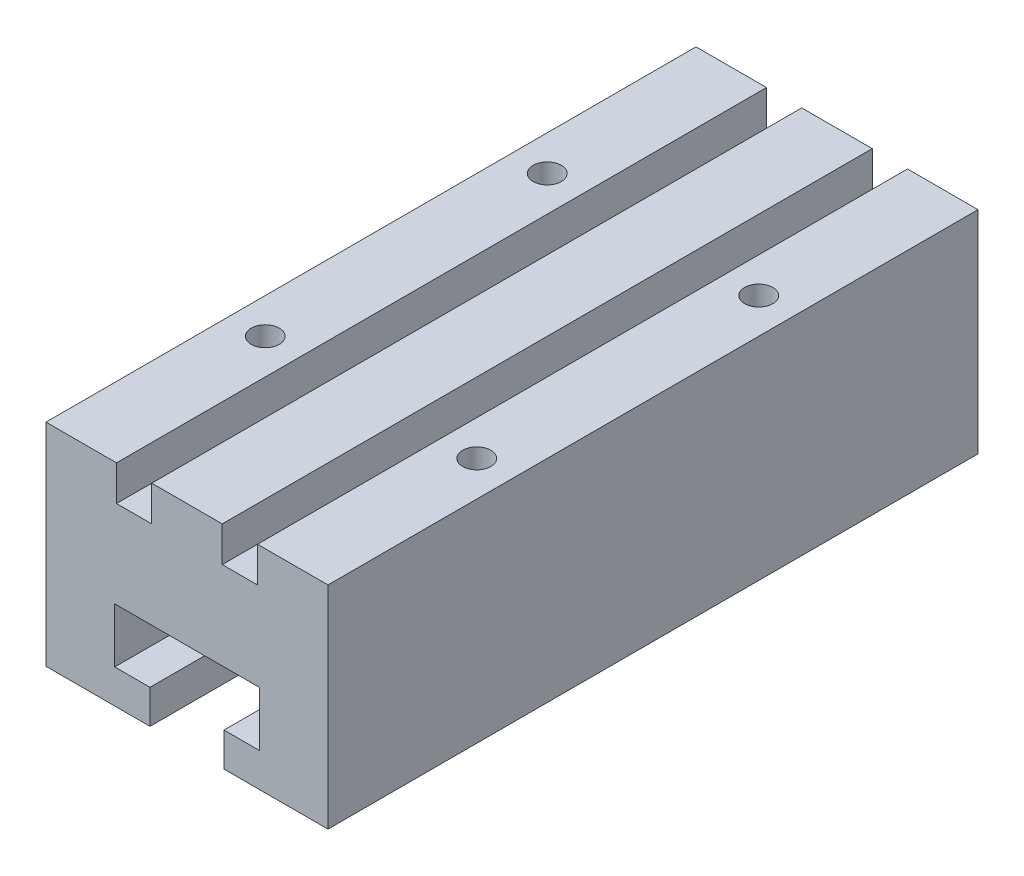
SolidWorks part; units mm, degrees
material "Acero al carbono no aleado"
ref_plane "Front" through (0, 0, 0) normal (0, 0, 1) x (1, 0, 0)
ref_plane "Top" through (0, 0, 0) normal (0, 1, 0) x (1, 0, 0)
ref_plane "Right" through (0, 0, 0) normal (1, 0, 0) x (0, 0, -1)
sketch "Croquis1" plane through (0, 0, 0) normal (0, 0, 1) x (1, 0, 0)
  line L1 (-20, -15) -> (20, -15)
  line L2 (-20, -15) -> (-20, 15)
  line L3 (-20, 15) -> (20, 15)
  line L4 (20, -15) -> (20, 15)
  line L5 (-20, -15) -> (20, 15) construction
  line L6 (-20, 15) -> (20, -15) construction
  point P0 (0, 0)
  dimension "D1" = 30
  dimension "D2" = 40
extrude "Saliente-Extruir1" add sketch "Croquis1" along normal blind 92.2
sketch "Croquis2" plane through (0, 0, 92.2) normal (0, 0, 1) x (1, 0, 0)
  line L0 (-10.25, -2.45) -> (-10.25, -10.2)
  line L3 (-10.25, -10.2) -> (-5.25, -10.2)
  line L4 (-5.25, -10.2) -> (-5.25, -15)
  line L5 (-20, -15) -> (20, -15) construction
  line L6 (5.25, -10.2) -> (5.25, -15)
  line L7 (0, 0) -> (0, 5.2378) construction
  line L8 (-10.25, -2.45) -> (10.25, -2.45)
  line L9 (10.25, -2.45) -> (10.25, -10.2)
  line L10 (10.25, -10.2) -> (5.25, -10.2)
  line L11 (-5.25, -15) -> (5.25, -15)
  dimension "D1" = 20.5
  dimension "D2" = 10.5
  dimension "D3" = 4.8
  dimension "D4" = 7.75
extrude "Cortar-Extruir1" cut sketch "Croquis2" against normal through all
chamfer "Chaflán1" [suppressed] distance 1 angle 45
sketch "Croquis3" plane through (0, 15, 0) normal (0, 1, 0) x (1, 0, 0)
  line L0 (20, 0) -> (-20, 0) construction
  line L1 (20, -92.2) -> (-20, -92.2) construction
  line L2 (-5, -92.2) -> (-10, -92.2)
  line L3 (-5, -92.2) -> (-5, 0)
  line L4 (-5, 0) -> (-10, 0)
  line L5 (-10, -92.2) -> (-10, 0)
  line L6 (5, 0) -> (10, 0)
  line L7 (5, 0) -> (5, -92.2)
  line L8 (5, -92.2) -> (10, -92.2)
  line L9 (10, 0) -> (10, -92.2)
  line L10 (0, 0) -> (0, -104.9846) construction
  dimension "D1" = 5
  dimension "D2" = 10
extrude "Cortar-Extruir2" cut sketch "Croquis3" against normal blind 5
sketch "Croquis4" plane through (0, 15, 0) normal (0, 1, 0) x (1, 0, 0)
  line L0 (-15, 0) -> (-15, -92.2) construction
  line L1 (-10, 0) -> (-20, 0) construction
  line L2 (-10, -92.2) -> (-20, -92.2) construction
  line L3 (-20, -46.1) -> (20, -46.1) construction
  line L4 (-20, -92.2) -> (-20, 0) construction
  line L5 (20, -92.2) -> (20, 0) construction
  line L6 (0, -46.1) -> (0, 0) construction
  circle A0 centre (-15, -26.1) radius 2
  circle A1 centre (-15, -66.1) radius 2
  circle A2 centre (15, -66.1) radius 2
  circle A3 centre (15, -26.1) radius 2
  dimension "D1" = 4
  dimension "D2" = 40
extrude "Cortar-Extruir3" cut sketch "Croquis4" against normal blind 10
chamfer "Chaflán2" [suppressed] distance 2 angle 45
chamfer "Chaflán3" [suppressed] distance 1 angle 45
